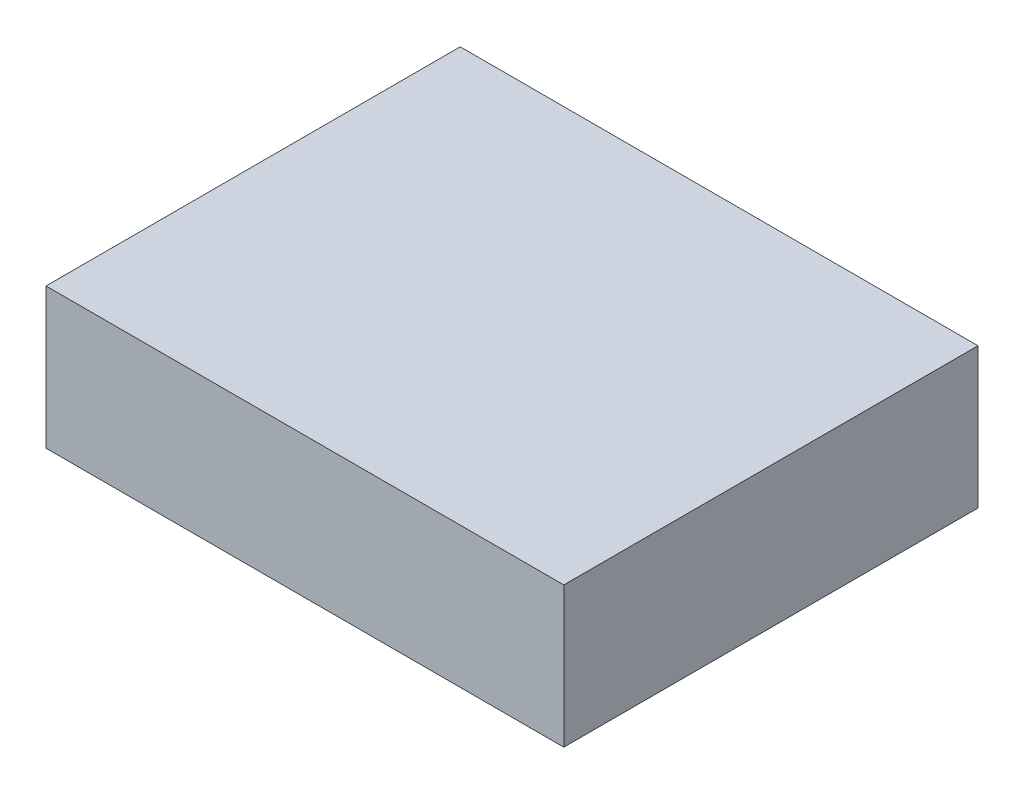
SolidWorks part; units mm, degrees
ref_plane "前视基准面" through (0, 0, 0) normal (0, 0, 1) x (1, 0, 0)
ref_plane "上视基准面" through (0, 0, 0) normal (0, 1, 0) x (1, 0, 0)
ref_plane "右视基准面" through (0, 0, 0) normal (1, 0, 0) x (0, 0, -1)
sketch "草图1" plane through (0, 0, 0) normal (0, 1, 0) x (1, 0, 0)
  line L1 (0, 0) -> (70, 0)
  line L2 (0, 0) -> (0, 56)
  line L3 (0, 56) -> (70, 56)
  line L4 (70, 0) -> (70, 56)
  dimension "D1" = 70
  dimension "D2" = 56
extrude "凸台-拉伸1" add sketch "草图1" along normal blind 19
